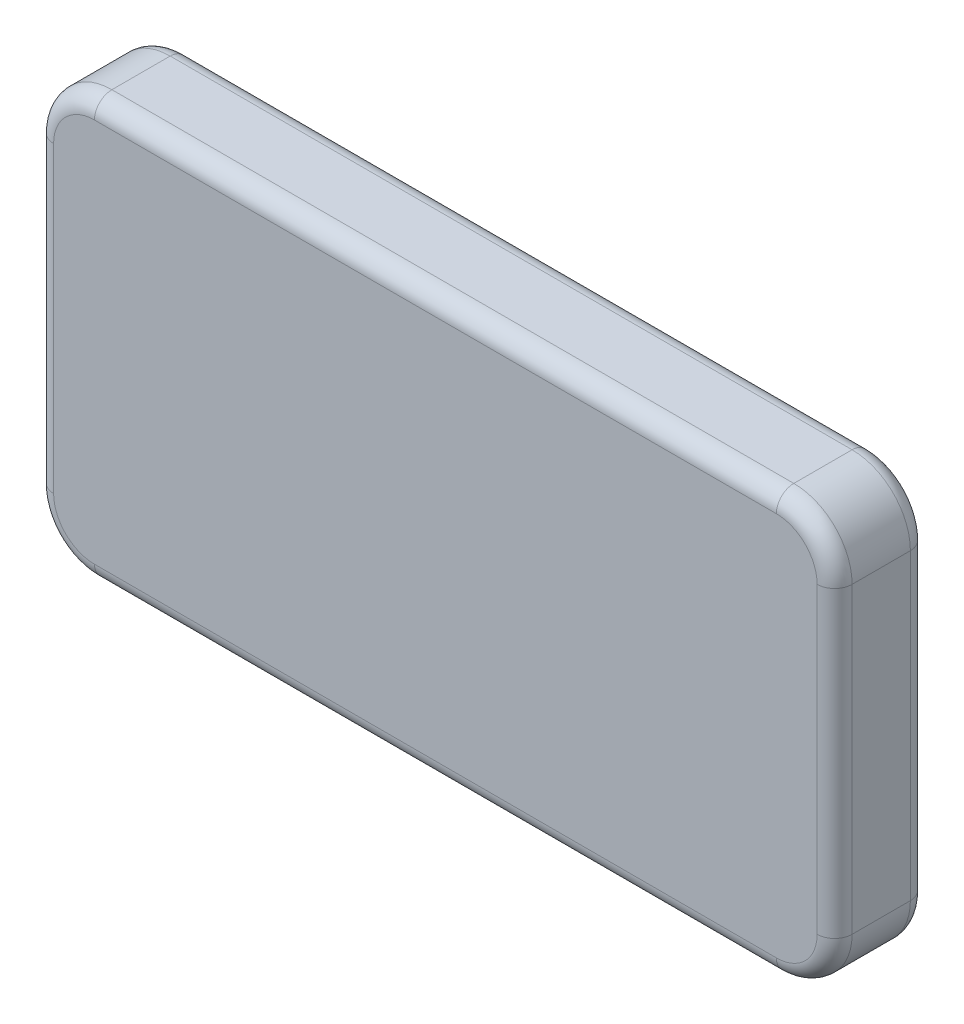
SolidWorks part; units mm, degrees
ref_plane "Front Plane" through (0, 0, 0) normal (0, 0, 1) x (1, 0, 0)
ref_plane "Top Plane" through (0, 0, 0) normal (0, 1, 0) x (1, 0, 0)
ref_plane "Right Plane" through (0, 0, 0) normal (1, 0, 0) x (0, 0, -1)
sketch "Sketch1" plane through (0, 0, 0) normal (0, 0, 1) x (1, 0, 0)
  line L1 (0, 0) -> (-137, 0)
  line L2 (0, 0) -> (0, 72)
  line L3 (0, 72) -> (-137, 72)
  line L4 (-137, 0) -> (-137, 72)
  dimension "D1" = 72
  dimension "D2" = 137
extrude "Boss-Extrude1" add sketch "Sketch1" along normal blind 16
sketch "Sketch2" plane through (-137, 0, 0) normal (-1, 0, 0) x (0, 0, 1)
  line L0 (8, 76.962) -> (8, -14.0493) construction
  line L1 (5.5, 59) -> (10.5, 59)
  line L2 (5.5, 59) -> (5.5, 46.5)
  line L3 (5.5, 46.5) -> (10.5, 46.5)
  line L4 (10.5, 59) -> (10.5, 46.5)
  line L5 (16, 72) -> (0, 72) construction
  line L6 (-6.5283, 36) -> (25.8897, 36) construction
  line L7 (5.5, 25.5) -> (10.5, 25.5)
  line L8 (5.5, 25.5) -> (5.5, 13)
  line L9 (5.5, 13) -> (10.5, 13)
  line L10 (10.5, 25.5) -> (10.5, 13)
  line L11 (16, 72) -> (16, 0) construction
  point P8 (8, 72)
  point P9 (8, 59)
  point P14 (8, 25.5)
  point P19 (16, 36)
  dimension "D1" = 5
  dimension "D2" = 12.5
  dimension "D3" = 21
  dimension "D4" = 12.5
  dimension "D5" = 10.5
extrude "Cut-Extrude1" cut sketch "Sketch2" against normal blind 12
fillet "Fillet1" radius 10 4 edges at (-137, 0, 8) (0, 0, 8) (0, 72, 8) (-137, 72, 8)
fillet "Fillet2" radius 3 8 edges at (-2.9289, 2.9289, 0) (0, 36, 0) (-2.9289, 69.0711, 0) (-68.5, 72, 0) (-134.0711, 69.0711, 0) (-137, 36, 0) (-134.0711, 2.9289, 0) (-68.5, 0, 0)
fillet "Fillet3" radius 3 8 edges at (-134.0711, 69.0711, 16) (-68.5, 72, 16) (-2.9289, 69.0711, 16) (0, 36, 16) (-2.9289, 2.9289, 16) (-68.5, 0, 16) (-134.0711, 2.9289, 16) (-137, 36, 16)
